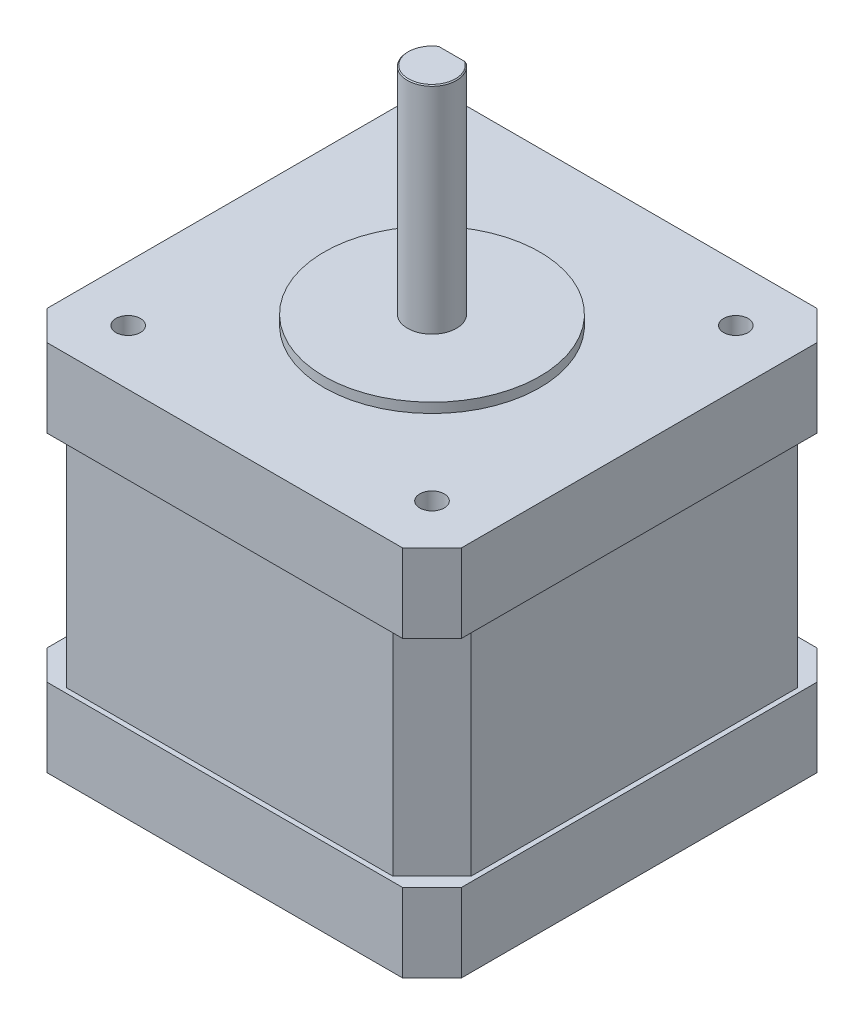
SolidWorks part; units mm, degrees
material "合金钢"
ref_plane "前视基准面" through (0, 0, 0) normal (0, 0, 1) x (1, 0, 0)
ref_plane "上视基准面" through (0, 0, 0) normal (0, 1, 0) x (1, 0, 0)
ref_plane "右视基准面" through (0, 0, 0) normal (1, 0, 0) x (0, 0, -1)
other "Configuration Table"
sketch "草图2" plane through (0, 0, 0) normal (0, 1, 0) x (1, 0, 0)
  line L1 (-21.15, 21.15) -> (21.15, 21.15)
  line L2 (-21.15, 21.15) -> (-21.15, -21.15)
  line L3 (-21.15, -21.15) -> (21.15, -21.15)
  line L4 (21.15, 21.15) -> (21.15, -21.15)
  line L5 (-21.15, 21.15) -> (21.15, -21.15) construction
  line L6 (-21.15, -21.15) -> (21.15, 21.15) construction
  point P0 (0, 0)
  dimension "D1" = 42.3
  dimension "D2" = 42.3
extrude "凸台-拉伸2" add sketch "草图2" along normal blind 8
chamfer "倒角1" distance 3 angle 45 4 edges at (-21.15, 4, -21.15) (21.15, 4, -21.15) (-21.15, 4, 21.15) (21.15, 4, 21.15)
sketch "草图3" plane through (0, 8, 0) normal (0, 1, 0) x (1, 0, 0)
  line L1 (-21.15, 21.15) -> (21.15, 21.15)
  line L2 (-21.15, 21.15) -> (-21.15, -21.15)
  line L3 (-21.15, -21.15) -> (21.15, -21.15)
  line L4 (21.15, 21.15) -> (21.15, -21.15)
  line L5 (-21.15, 21.15) -> (21.15, -21.15) construction
  line L6 (-21.15, -21.15) -> (21.15, 21.15) construction
  point P0 (0, 0)
  dimension "D1" = 42.3
  dimension "D2" = 42.3
extrude "凸台-拉伸3" add sketch "草图3" along normal blind 22
sketch "草图4" plane through (0, 30, 0) normal (0, 1, 0) x (1, 0, 0)
  line L8 (-21.15, 18.15) -> (-21.15, -18.15)
  line L9 (-18.15, 21.15) -> (-21.15, 18.15)
  line L10 (18.15, 21.15) -> (-18.15, 21.15)
  line L11 (21.15, 18.15) -> (18.15, 21.15)
  line L12 (21.15, -18.15) -> (21.15, 18.15)
  line L13 (18.15, -21.15) -> (21.15, -18.15)
  line L14 (-18.15, -21.15) -> (18.15, -21.15)
  line L15 (-21.15, -18.15) -> (-18.15, -21.15)
  line L16 (-21.15, 18.15) -> (-21.15, -18.15)
  line L17 (-18.15, 21.15) -> (-21.15, 18.15)
  line L18 (18.15, 21.15) -> (-18.15, 21.15)
  line L19 (21.15, 18.15) -> (18.15, 21.15)
  line L20 (21.15, -18.15) -> (21.15, 18.15)
  line L21 (18.15, -21.15) -> (21.15, -18.15)
  line L22 (-18.15, -21.15) -> (18.15, -21.15)
  line L23 (-21.15, -18.15) -> (-18.15, -21.15)
  dimension "D1" = 0
extrude "凸台-拉伸4" add sketch "草图4" along normal blind 8
sketch "草图5" plane through (0, 30, 0) normal (0, 1, 0) x (1, 0, 0)
  line L0 (-16.15, 21.15) -> (-21.15, 21.15)
  line L1 (18.15, 21.15) -> (-18.15, 21.15) construction
  line L2 (-21.15, 21.15) -> (-21.15, 16.15)
  line L3 (-21.15, 18.15) -> (-21.15, -18.15) construction
  line L4 (-21.15, 16.15) -> (-16.15, 21.15)
  dimension "D1" = 5
  dimension "D2" = 5
extrude "切除-拉伸1" cut sketch "草图5" along direction (0, 1, 0) on the side against the normal up to surface (22 mm away) contours L4 L0 L2
sketch "草图6" plane through (0, 38, 0) normal (0, 1, 0) x (1, 0, 0)
  line L0 (-21.15, 16.15) -> (-21.15, 21.15)
  line L1 (-21.15, 21.15) -> (-16.15, 21.15)
  line L2 (-21.15, -16.15) -> (-21.15, -21.15)
  line L3 (-21.15, 18.15) -> (-21.15, -18.15) construction
  line L4 (-21.15, 18.15) -> (-21.15, 16.15)
  line L5 (-21.15, 16.15) -> (-16.15, 21.15)
  line L6 (-16.15, 21.15) -> (-18.15, 21.15)
  line L7 (-18.15, 21.15) -> (-21.15, 18.15)
  line L8 (-21.15, 18.15) -> (-21.15, 16.15)
  line L9 (-21.15, 16.15) -> (-16.15, 21.15)
  line L10 (-16.15, 21.15) -> (-18.15, 21.15)
  line L11 (-18.15, 21.15) -> (-21.15, 18.15)
  line L12 (-21.15, -21.15) -> (-16.15, -21.15)
  line L13 (-18.15, -21.15) -> (18.15, -21.15) construction
  line L14 (-16.15, -21.15) -> (-21.15, -16.15)
  line L15 (21.15, -16.15) -> (21.15, -21.15)
  line L16 (21.15, -18.15) -> (21.15, 18.15) construction
  line L17 (21.15, -21.15) -> (16.15, -21.15)
  line L18 (16.15, -21.15) -> (21.15, -16.15)
  line L19 (21.15, 21.15) -> (16.15, 21.15)
  line L20 (18.15, 21.15) -> (-18.15, 21.15) construction
  line L21 (16.15, 21.15) -> (21.15, 16.15)
  line L22 (21.15, 16.15) -> (21.15, 21.15)
  circle A1 centre (0, 0) radius 2.5
  line M1 (-21.15, -18.15) -> (-18.15, -21.15)
  line M2 (-18.15, -21.15) -> (18.15, -21.15)
  line M3 (18.15, -21.15) -> (21.15, -18.15)
  line M4 (21.15, -18.15) -> (21.15, 18.15)
  line M5 (21.15, 18.15) -> (18.15, 21.15)
  line M6 (18.15, 21.15) -> (-18.15, 21.15)
  line M8 (-21.15, 18.15) -> (-21.15, -18.15)
  dimension "D1" = 0
  dimension "D2" = 5
  dimension "D3" = 5
  dimension "D4" = 5
  dimension "D5" = 5
  dimension "D6" = 5
  dimension "D7" = 5
extrude "切除-拉伸4" cut sketch "草图6" against normal blind 22 from surface at -8 contours L14 M2 M8 M1 | L2 L12 M1 | L18 M2 M3 M4 | L17 L15 M3 | L21 M6 M4 M5 | L22 L19 M5 starting at face at (-20.15, 30, 20.15)
sketch "草图7" plane through (0, 38, 0) normal (0, 1, 0) x (1, 0, 0)
  circle A0 centre (0, 0) radius 11
  dimension "D1" = 22
extrude "凸台-拉伸5" add sketch "草图7" along normal blind 1
sketch "草图8" plane through (0, 39, 0) normal (0, 1, 0) x (1, 0, 0)
  circle A0 centre (0, 0) radius 2.5
  dimension "D1" = 5
extrude "凸台-拉伸6" add sketch "草图8" along normal blind 22
sketch "草图9" plane through (0, 61, 0) normal (0, 1, 0) x (1, 0, 0)
  line L0 (-1.5, 2) -> (1.5, 2)
  circle A0 centre (0, 0) radius 2.5 construction
  circle A2 centre (0, 0) radius 2.5
  circle A3 centre (0, 0) radius 2.5
  circle M3 centre (0, 0) radius 2.5
  dimension "D1" = 0
  dimension "D2" = 4.5
extrude "切除-拉伸6" cut sketch "草图9" against normal blind 18 contours L0 M3
sketch "草图10" plane through (0, 38, 0) normal (0, 1, 0) x (1, 0, 0)
  line L1 (-15.5, 15.5) -> (15.5, 15.5)
  line L2 (-15.5, 15.5) -> (-15.5, -15.5)
  line L3 (-15.5, -15.5) -> (15.5, -15.5)
  line L4 (15.5, 15.5) -> (15.5, -15.5)
  line L5 (-15.5, 15.5) -> (15.5, -15.5) construction
  line L6 (-15.5, -15.5) -> (15.5, 15.5) construction
  point P0 (0, 0)
  dimension "D1" = 31
  dimension "D2" = 31
hole_wizard "M3 螺纹孔1" positions "草图11" profile "草图12" tap size "M3" standard "GB" end condition through all
sketch "草图11" plane through (0, 38, 0) normal (0, 1, 0) x (1, 0, 0)
  point P0 (-15.5, 15.5)
  point P3 (15.5, 15.5)
  point P6 (15.5, -15.5)
  point P9 (-15.5, -15.5)
sketch "草图12" plane through (-15.5, 38, -15.5) normal (1, 0, 0) x (0, 0, 1)
  line L0 (0, 0) -> (0, 38)
  line L1 (0, 38) -> (1.25, 38)
  line L2 (1.25, 38) -> (1.25, 0)
  line L5 (1.25, 0) -> (0, 0)
  line L11 (0, -6.35) -> (0, 107.95) construction
  dimension "通孔螺纹孔钻头直径" = 2.5
  dimension "通孔螺纹孔钻头深度" = 38
cosmetic thread "孔螺蚊线1" parameters "D2"=3
cosmetic thread "孔螺蚊线2" parameters "D2"=3
cosmetic thread "孔螺蚊线3" parameters "D2"=3
cosmetic thread "孔螺蚊线4" parameters "D2"=3
sketch "草图15" plane through (-21.15, 0, 0) normal (-1, 0, 0) x (0, 0, 1)
  line L1 (21.1452, 8) -> (-21.15, 8)
  line L2 (21.1452, 8) -> (21.1452, 30)
  line L3 (21.1452, 30) -> (-21.15, 30)
  line L4 (-21.15, 8) -> (-21.15, 30)
  line L5 (21.1452, 8) -> (-21.15, 30) construction
  line L6 (21.1452, 30) -> (-21.15, 8) construction
  point P0 (-0.0024, 19)
  dimension "D1" = 19
  dimension "D2" = 22
extrude "切除-拉伸8" cut sketch "草图15" against normal blind 0.5
pattern_circular "阵列(圆周)1" count 4 every 90 about axis through (0, 0, 0) along (0, 1, 0) of "切除-拉伸8"
chamfer "倒角3" distance 0.1 angle 45 1 edges at (0, 61, 2.5)
